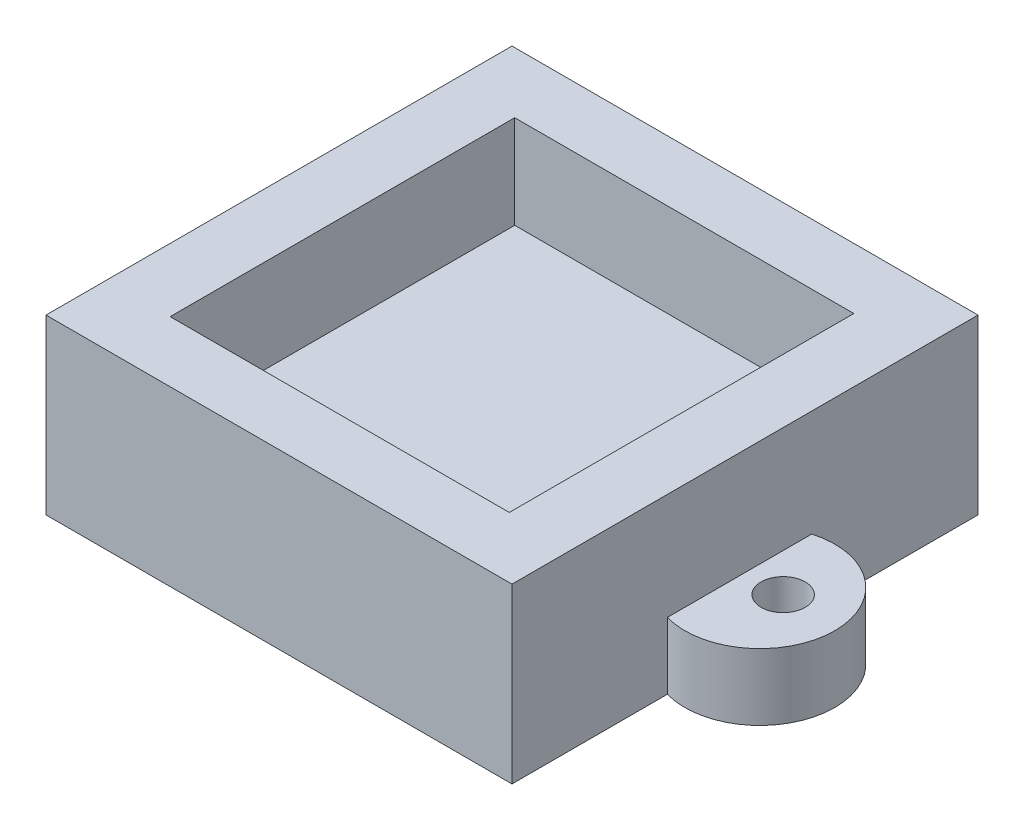
SolidWorks part; units mm, degrees
ref_plane "Front Plane" through (0, 0, 0) normal (0, 0, 1) x (1, 0, 0)
ref_plane "Top Plane" through (0, 0, 0) normal (0, 1, 0) x (1, 0, 0)
ref_plane "Right Plane" through (0, 0, 0) normal (1, 0, 0) x (0, 0, -1)
sketch "Sketch1" plane through (0, 0, 0) normal (0, 1, 0) x (1, 0, 0)
  line L1 (17.5, -17.5) -> (-17.5, -17.5)
  line L2 (17.5, -17.5) -> (17.5, 17.5)
  line L3 (17.5, 17.5) -> (-17.5, 17.5)
  line L4 (-17.5, -17.5) -> (-17.5, 17.5)
  line L5 (17.5, -17.5) -> (-17.5, 17.5) construction
  line L6 (17.5, 17.5) -> (-17.5, -17.5) construction
  point P0 (0, 0)
  dimension "D1" = 35
  dimension "30" = 35
extrude "Boss-Extrude1" add sketch "Sketch1" along normal blind 13
sketch "Sketch2" plane through (0, 13, 0) normal (0, 1, 0) x (1, 0, 0)
  line L1 (12.7356, -12.94) -> (-12.7356, -12.94)
  line L2 (12.7356, -12.94) -> (12.7356, 12.94)
  line L3 (12.7356, 12.94) -> (-12.7356, 12.94)
  line L4 (-12.7356, -12.94) -> (-12.7356, 12.94)
  line L5 (12.7356, -12.94) -> (-12.7356, 12.94) construction
  line L6 (12.7356, 12.94) -> (-12.7356, -12.94) construction
  point P0 (0, 0)
extrude "Cut-Extrude1" cut sketch "Sketch2" against normal blind 7
sketch "Sketch3" plane through (0, 0, 0) normal (0, -1, 0) x (1, 0, 0)
  line L0 (-17.5, -17.5) -> (-17.5, 17.5) construction
  line L1 (-17.5, 17.5) -> (-17.5, 5.8332)
  line L2 (0, -17.5) -> (0, 17.5)
  line L5 (-17.5, 17.5) -> (-17.5, -17.5)
  line L6 (-17.5, -17.5) -> (17.5, -17.5)
  line L7 (17.5, -17.5) -> (17.5, 17.5)
  line L8 (17.5, 17.5) -> (-17.5, 17.5)
  line L9 (-17.5, -5.0156) -> (-17.5, -17.5)
  line L10 (-17.5, -17.5) -> (17.5, -17.5)
  line L11 (17.5, -17.5) -> (17.5, 17.5)
  line L12 (17.5, 17.5) -> (-17.5, 17.5)
  arc A0 (-17.5, 5.8332) -> (-17.5, -5.0156) centre (-19.0196, 0.4088) ccw
  arc A1 (17.5, 5.8332) -> (17.5, -5.0156) centre (19.0196, 0.4088) cw
  point P12 (0, 0)
  line M6 (-17.5, 17.5) -> (-17.5, -17.5)
  dimension "D1" = 0
extrude "Boss-Extrude2" add sketch "Sketch3" against normal blind 5 contours A0 M6 | A1 L11
sketch "Sketch5" plane through (0, 0, 0) normal (0, -1, 0) x (1, 0, 0)
  line L0 (0, -17.5) -> (0, 17.5)
  line L1 (-17.5, 17.5) -> (17.5, 17.5) construction
  circle A0 centre (-20.3674, 0) radius 1.6591
  circle A1 centre (20.3674, 0) radius 1.6591
  point P8 (0, 0)
extrude "Cut-Extrude2" cut sketch "Sketch5" against normal through all contours A0 | A1
